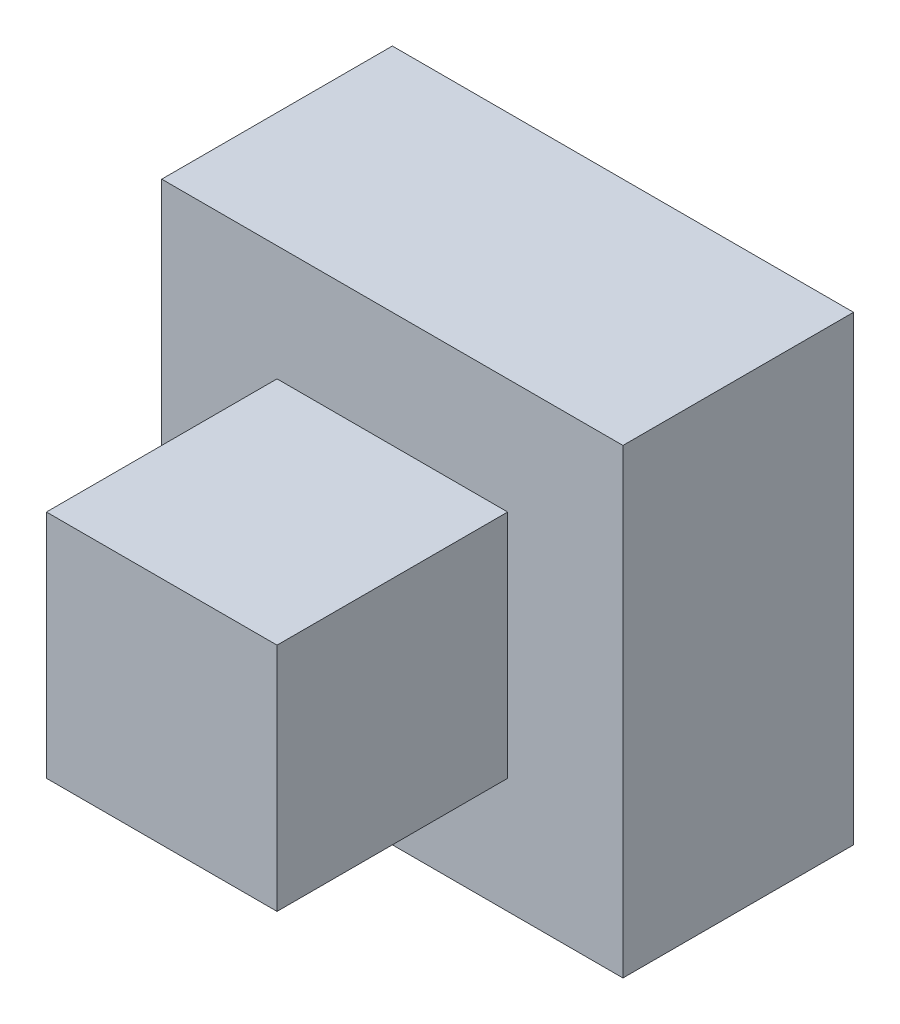
SolidWorks part; units mm, degrees
ref_plane "前视基准面" through (0, 0, 0) normal (0, 0, 1) x (1, 0, 0)
ref_plane "上视基准面" through (0, 0, 0) normal (0, 1, 0) x (1, 0, 0)
ref_plane "右视基准面" through (0, 0, 0) normal (1, 0, 0) x (0, 0, -1)
other "Configuration Table"
sketch "草图1" plane through (0, 0, 0) normal (0, 0, 1) x (1, 0, 0)
  line L1 (0, 0) -> (20, 0)
  line L2 (0, 0) -> (0, 20)
  line L3 (0, 20) -> (20, 20)
  line L4 (20, 0) -> (20, 20)
extrude "BaseBox" add sketch "草图1" along normal blind 10
sketch "草图2" plane through (0, 0, 10) normal (0, 0, 1) x (1, 0, 0)
  line L1 (5, 5) -> (15, 5)
  line L2 (5, 5) -> (5, 15)
  line L3 (5, 15) -> (15, 15)
  line L4 (15, 5) -> (15, 15)
extrude "DraftDir2" add sketch "草图2" along normal blind 10 and the other way blind 5 draft 3
